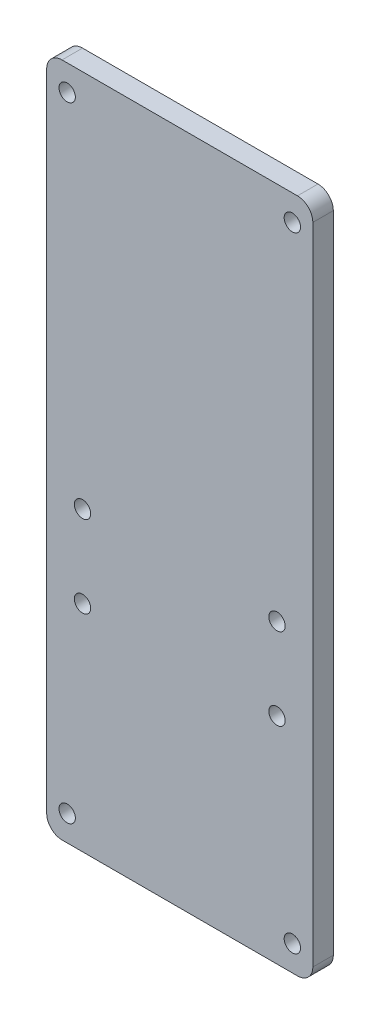
SolidWorks part; units mm, degrees
material "Acrylic (Medium-high impact)"
ref_plane "Front Plane" through (0, 0, 0) normal (0, 0, 1) x (1, 0, 0)
ref_plane "Top Plane" through (0, 0, 0) normal (0, 1, 0) x (1, 0, 0)
ref_plane "Right Plane" through (0, 0, 0) normal (1, 0, 0) x (0, 0, -1)
sketch "Sketch1" plane through (0, 0, 0) normal (0, 0, 1) x (1, 0, 0)
  line L0 (1.25, 61.9364) -> (93.1655, 61.9364) construction
  line L1 (23.2069, 124.9364) -> (23.2069, -1.0636)
  line L2 (26.2069, 127.9364) -> (72.2085, 127.9364)
  line L3 (71.2085, 0.9364) -> (71.2085, -12.0636) construction
  line L4 (26.2069, -4.0636) -> (72.2085, -4.0636)
  line L6 (30.2077, 53.9364) -> (68.2077, 53.9364) construction
  line L7 (30.2077, 53.9364) -> (30.2077, 37.9364) construction
  line L8 (49.2077, -12.0636) -> (49.2077, 135.9364) construction
  line L9 (30.2077, 37.9364) -> (68.2077, 37.9364) construction
  line L10 (68.2077, 53.9364) -> (68.2077, 37.9364) construction
  line L20 (75.2085, 124.9364) -> (75.2085, -1.0636)
  circle A0 centre (30.2077, 53.9364) radius 1.6
  circle A1 centre (27.2069, 0.9364) radius 1.6
  arc A2 (26.2069, -4.0636) -> (23.2069, -1.0636) centre (26.2069, -1.0636) cw
  circle A3 centre (30.2077, 37.9364) radius 1.6
  arc A4 (72.2085, -4.0636) -> (75.2085, -1.0636) centre (72.2085, -1.0636) ccw
  circle A5 centre (71.2085, 122.9364) radius 1.6
  arc A6 (72.2085, 127.9364) -> (75.2085, 124.9364) centre (72.2085, 124.9364) cw
  circle A7 centre (71.2085, 0.9364) radius 1.6
  arc A8 (26.2069, 127.9364) -> (23.2069, 124.9364) centre (26.2069, 124.9364) ccw
  circle A9 centre (68.2077, 53.9364) radius 1.6
  circle A10 centre (27.2069, 122.9364) radius 1.6
  circle A11 centre (68.2077, 37.9364) radius 1.6
  point P10 (23.2069, 61.9364)
  point P13 (49.2077, 127.9364)
  point P14 (49.2077, -4.0636)
  point P30 (75.2085, 61.9364)
  dimension "D5" = 22.0008
  dimension "D17" = 3
  dimension "D6" = 3.2
  dimension "D7" = 8
  dimension "D8" = 19
  dimension "D2" = 26.0008
  dimension "D3" = 66
  dimension "D4" = 61
  dimension "D9" = 16
extrude "Boss-Extrude1" add sketch "Sketch1" along normal blind 4
